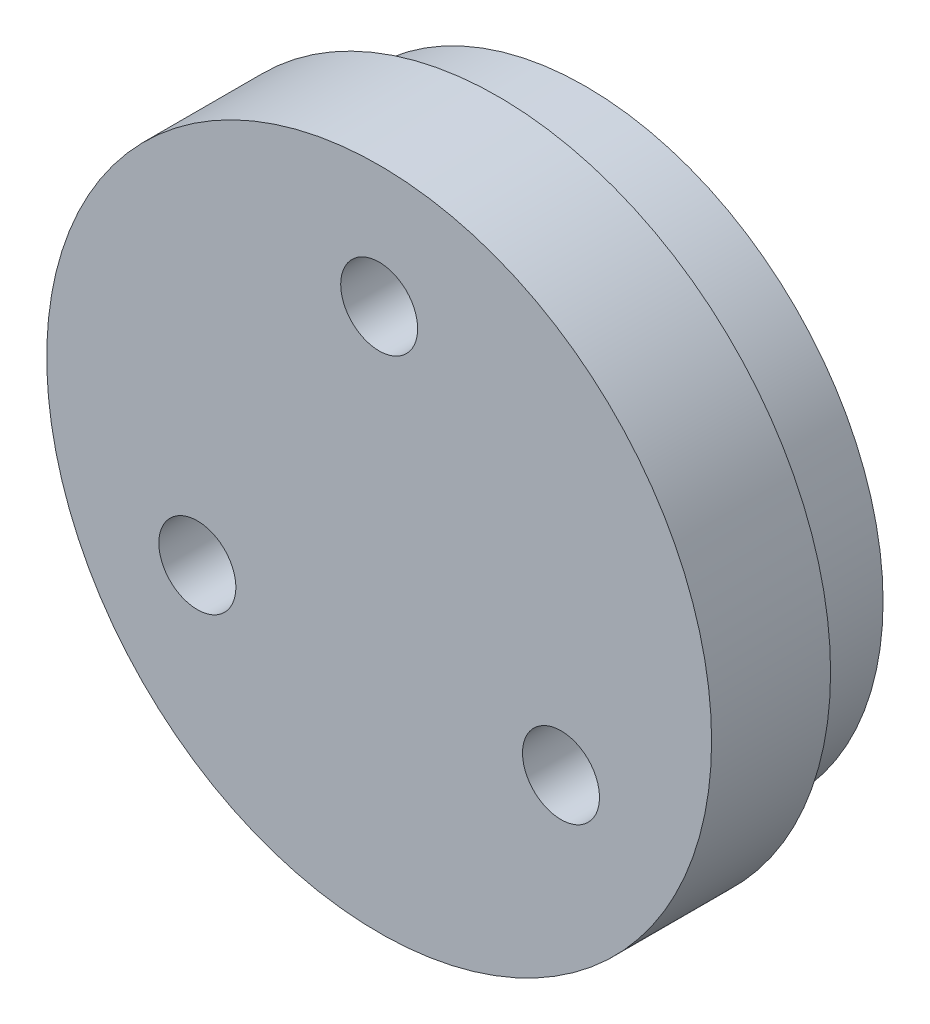
SolidWorks part; units mm, degrees
material "ABS"
ref_plane "正面" through (0, 0, 0) normal (0, 0, 1) x (1, 0, 0)
ref_plane "平面" through (0, 0, 0) normal (0, 1, 0) x (1, 0, 0)
ref_plane "右側面" through (0, 0, 0) normal (1, 0, 0) x (0, 0, -1)
sketch "ｽｹｯﾁ1" plane through (0, 0, 0) normal (0, 0, 1) x (1, 0, 0)
  circle A0 centre (0, 0) radius 8.5
  dimension "D1" = 17
extrude "ﾎﾞｽ - 押し出し1" add sketch "ｽｹｯﾁ1" along normal blind 2.5
sketch "ｽｹｯﾁ2" plane through (0, 0, 2.5) normal (0, 0, 1) x (1, 0, 0)
  circle A0 centre (0, 0) radius 9.5
  dimension "D1" = 19
extrude "ﾎﾞｽ - 押し出し2" add sketch "ｽｹｯﾁ2" along normal blind 3.4
sketch "ｽｹｯﾁ3" plane through (0, 0, 0) normal (0, 0, -1) x (-1, 0, 0)
  circle A0 centre (0, 0) radius 6 construction
  circle A1 centre (0, 6) radius 1.1
  circle A2 centre (5.1962, -3) radius 1.1
  circle A3 centre (-5.1962, -3) radius 1.1
  point P6 (-5.1963, -2.9997)
  point P7 (5.2075, -2.9803)
  point P11 (0, 0)
  dimension "D1" = 12
  dimension "D2" = 2.2
  dimension "D3" = 3
extrude "ｶｯﾄ - 押し出し1" cut sketch "ｽｹｯﾁ3" against normal through all
